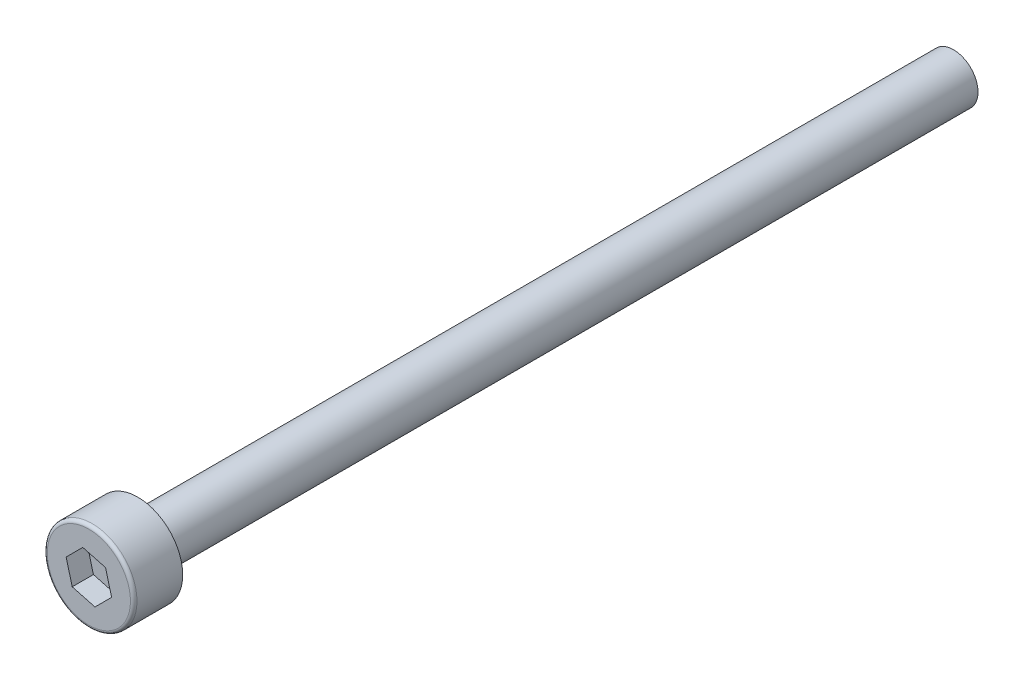
SolidWorks part; units mm, degrees
ref_plane "前视基准面" through (0, 0, 0) normal (0, 0, 1) x (1, 0, 0)
ref_plane "上视基准面" through (0, 0, 0) normal (0, 1, 0) x (1, 0, 0)
ref_plane "右视基准面" through (0, 0, 0) normal (1, 0, 0) x (0, 0, -1)
sketch "草图1" plane through (0, 0, 0) normal (0, 0, 1) x (1, 0, 0)
  circle A0 centre (0, 0) radius 2.75
  dimension "D1" = 5.5
extrude "凸台-拉伸1" add sketch "草图1" along normal blind 3
sketch "草图2" plane through (0, 0, 3) normal (0, 0, 1) x (1, 0, 0)
  line L1 (-1.0206, -1.0206) -> (0.3736, -1.3942)
  line L2 (0.3736, -1.3942) -> (1.3942, -0.3736)
  line L3 (1.3942, -0.3736) -> (1.0206, 1.0206)
  line L4 (1.0206, 1.0206) -> (-0.3736, 1.3942)
  line L5 (-0.3736, 1.3942) -> (-1.3942, 0.3736)
  line L6 (-1.3942, 0.3736) -> (-1.0206, -1.0206)
  circle A0 centre (0, 0) radius 1.25 construction
  dimension "D1" = 2.5
extrude "切除-拉伸1" cut sketch "草图2" against normal blind 1.3
sketch "草图3" plane through (0, 0, 0) normal (0, 0, -1) x (-1, 0, 0)
  circle A0 centre (0, 0) radius 1.5
  dimension "D1" = 3
extrude "凸台-拉伸2" add sketch "草图3" along normal blind 50
fillet "圆角1" radius 0.2 1 edges at (2.75, 0, 3)
